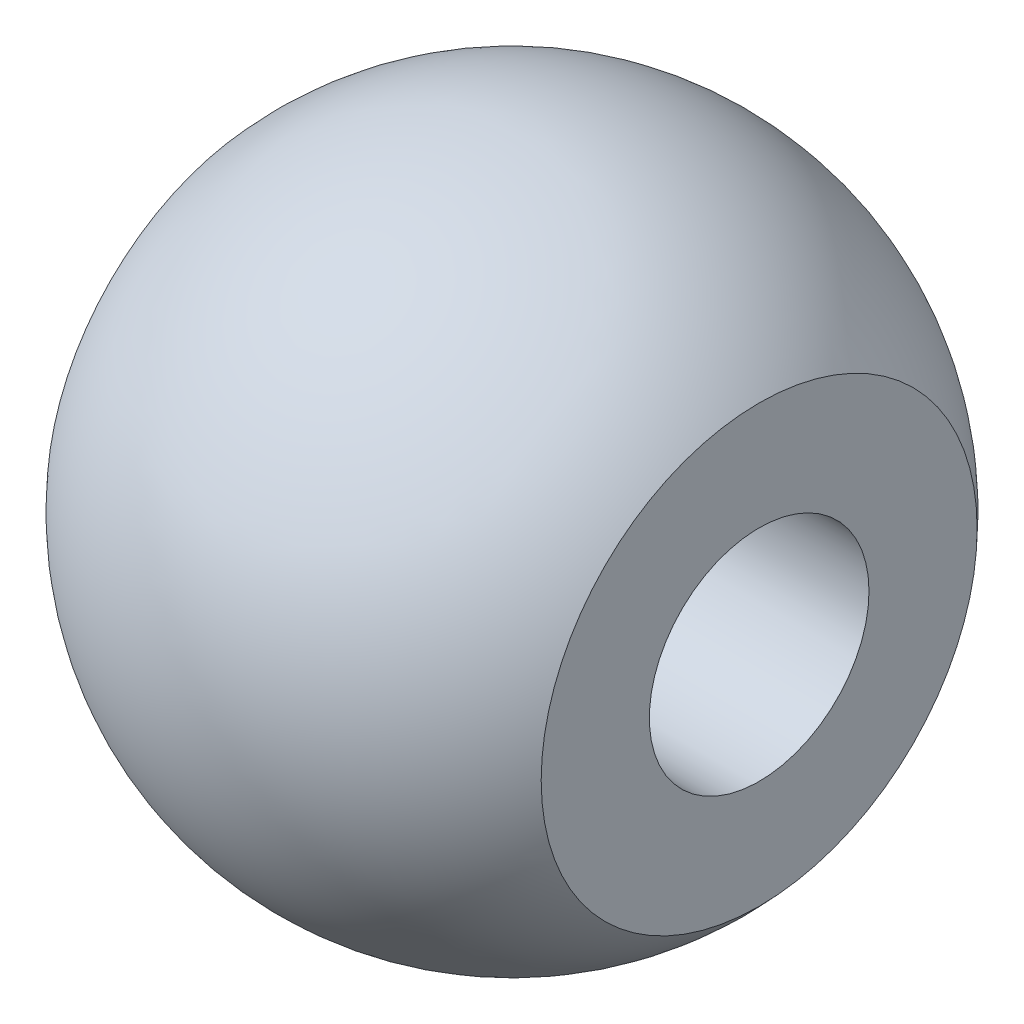
SolidWorks part; units mm, degrees
ref_plane "Front Plane" through (0, 0, 0) normal (0, 0, 1) x (1, 0, 0)
ref_plane "Top Plane" through (0, 0, 0) normal (0, 1, 0) x (1, 0, 0)
ref_plane "Right Plane" through (0, 0, 0) normal (1, 0, 0) x (0, 0, -1)
sketch "Sketch1" plane through (0, 0, 0) normal (0, 0, 1) x (1, 0, 0)
  line L2 (9, 0) -> (0, 0) construction
  line L3 (9, 3.9686) -> (9, 2)
  line L4 (9, 2) -> (1, 2)
  line L5 (1, 2) -> (0, 3.7321)
  line L6 (0, 3.7321) -> (0, 3.9686)
  arc A0 (0, 3.9686) -> (9, 3.9686) centre (4.5, 0) cw
  point P5 (0, 3.8503)
  point P9 (9, 5.8027)
  point P10 (9, 6.2518)
  point P12 (0, 0)
  dimension "D2" = 6
  dimension "D1" = 9
  dimension "D3" = 60
  dimension "D4" = 4
  dimension "D5" = 1
revolve "Revolve1" add sketch "Sketch1" angle 360 about L2
